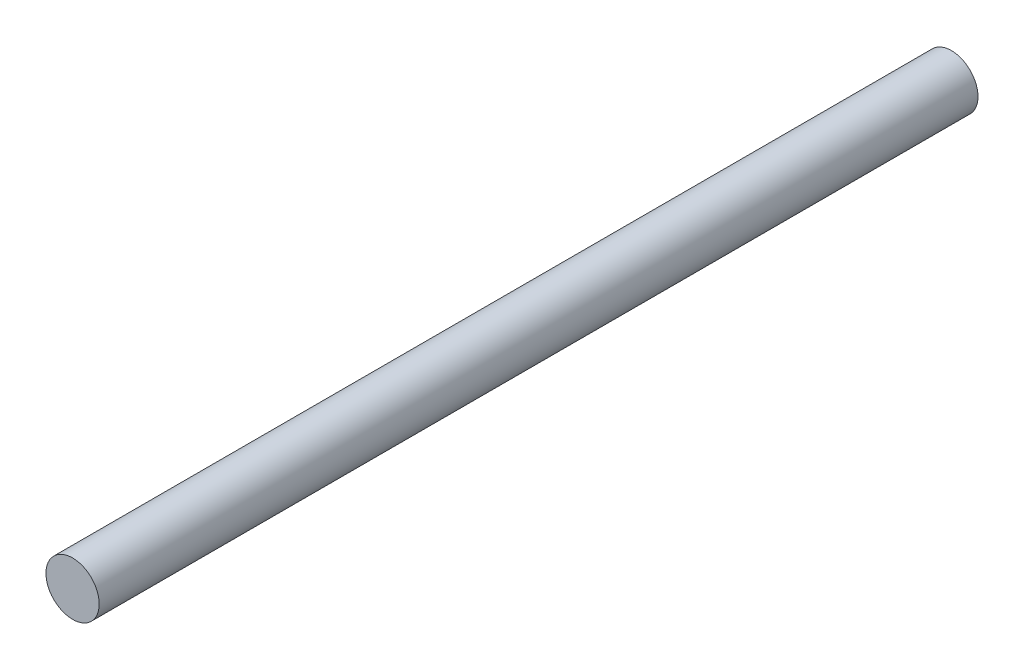
SolidWorks part; units mm, degrees
ref_plane "Front Plane" through (0, 0, 0) normal (0, 0, 1) x (1, 0, 0)
ref_plane "Top Plane" through (0, 0, 0) normal (0, 1, 0) x (1, 0, 0)
ref_plane "Right Plane" through (0, 0, 0) normal (1, 0, 0) x (0, 0, -1)
sketch "Sketch1" plane through (0, 0, 0) normal (0, 0, 1) x (1, 0, 0)
  circle A0 centre (0, 0) radius 1
  dimension "D1" = 2
extrude "Boss-Extrude1" add sketch "Sketch1" along normal blind 33
